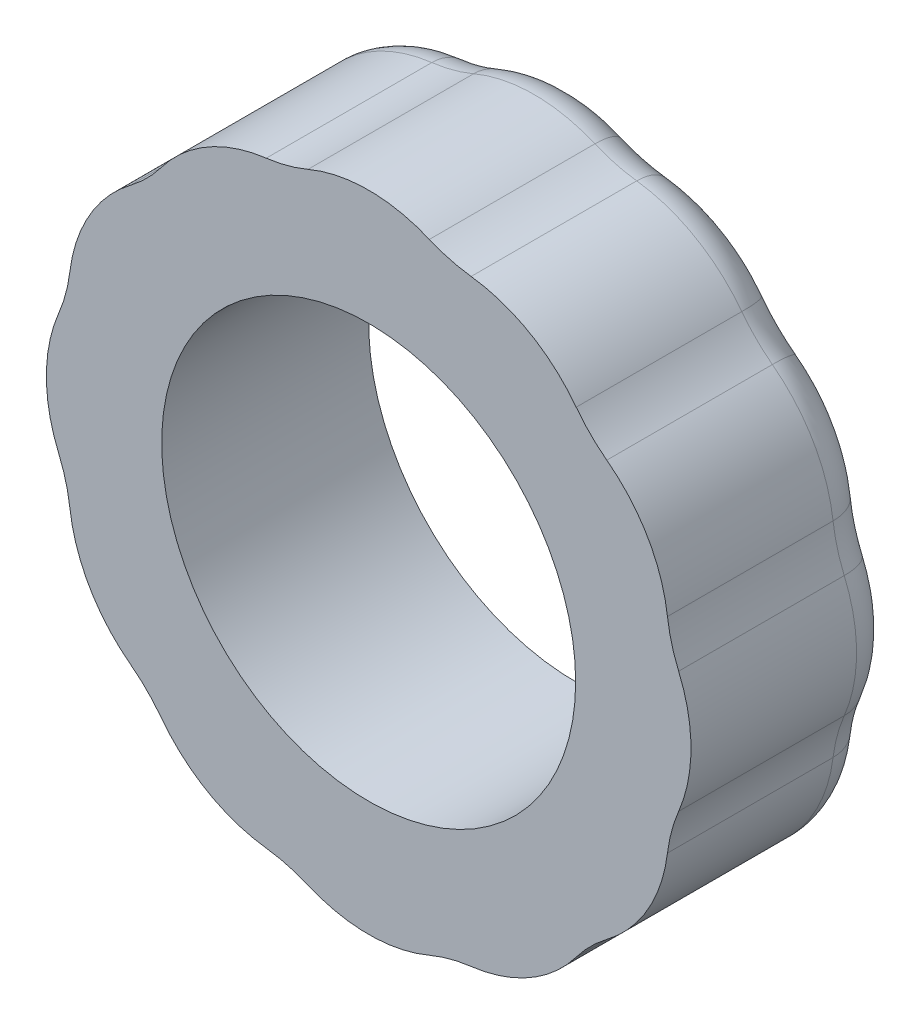
SolidWorks part; units mm, degrees
ref_plane "Front" through (0, 0, 0) normal (0, 0, 1) x (1, 0, 0)
ref_plane "Top" through (0, 0, 0) normal (0, 1, 0) x (1, 0, 0)
ref_plane "Right" through (0, 0, 0) normal (1, 0, 0) x (0, 0, -1)
sketch "Sketch1" plane through (0, 0, 0) normal (0, 0, 1) x (1, 0, 0)
  line L0 (0, 0) -> (0.3882, 1.4489) construction
  line L1 (0, 0) -> (-0.3882, 1.4489) construction
  line L2 (0, 0) -> (0, 1.5) construction
  circle A0 centre (0, 0) radius 1.5 construction
  circle A1 centre (0, 0) radius 1
  arc A2 (-0.3882, 1.4489) -> (0.3882, 1.4489) centre (0, 0.8072) cw
  arc A3 (0.3882, 1.4489) -> (1.0607, 1.0607) centre (0.4036, 0.699) cw
  arc A4 (1.0607, 1.0607) -> (1.4489, 0.3882) centre (0.699, 0.4036) cw
  arc A5 (1.4489, 0.3882) -> (1.4489, -0.3882) centre (0.8072, 0) cw
  arc A6 (1.4489, -0.3882) -> (1.0607, -1.0607) centre (0.699, -0.4036) cw
  arc A7 (1.0607, -1.0607) -> (0.3882, -1.4489) centre (0.4036, -0.699) cw
  arc A8 (0.3882, -1.4489) -> (-0.3882, -1.4489) centre (0, -0.8072) cw
  arc A9 (-0.3882, -1.4489) -> (-1.0607, -1.0607) centre (-0.4036, -0.699) cw
  arc A10 (-1.0607, -1.0607) -> (-1.4489, -0.3882) centre (-0.699, -0.4036) cw
  arc A11 (-1.4489, -0.3882) -> (-1.4489, 0.3882) centre (-0.8072, 0) cw
  arc A12 (-1.4489, 0.3882) -> (-1.0607, 1.0607) centre (-0.699, 0.4036) cw
  arc A13 (-1.0607, 1.0607) -> (-0.3882, 1.4489) centre (-0.4036, 0.699) cw
  point P43 (0, 0)
  dimension "D1" = 3
  dimension "D2" = 2
  dimension "D4" = 0.75
  dimension "D3" = 30
  dimension "D5" = 12
extrude "Boss-Extrude1" add sketch "Sketch1" along normal mid plane 1
fillet "Fillet1" radius 0.75 12 edges at (-1.4489, -0.3882, 0) (-1.0607, -1.0607, 0) (-0.3882, -1.4489, 0) (0.3882, -1.4489, 0) (1.4489, -0.3882, 0) (1.4489, 0.3882, 0) (1.0607, -1.0607, 0) (1.0607, 1.0607, 0) (0.3882, 1.4489, 0) (-0.3882, 1.4489, 0) (-1.0607, 1.0607, 0) (-1.4489, 0.3882, 0)
fillet "Fillet2" radius 0.2 24 edges at (1.4634, 0.3921, -0.5) (1.5572, 0, -0.5) (1.4634, -0.3921, -0.5) (1.3486, -0.7786, -0.5) (1.0713, -1.0713, -0.5) (0.7786, -1.3486, -0.5) (0.3921, -1.4634, -0.5) (0, -1.5572, -0.5) (-0.3921, -1.4634, -0.5) (-0.7786, -1.3486, -0.5) (-1.0713, -1.0713, -0.5) (-1.3486, -0.7786, -0.5) (-1.4634, -0.3921, -0.5) (-1.5572, 0, -0.5) (-1.4634, 0.3921, -0.5) (-1.3486, 0.7786, -0.5) (-1.0713, 1.0713, -0.5) (-0.7786, 1.3486, -0.5) (-0.3921, 1.4634, -0.5) (0, 1.5572, -0.5) (0.3921, 1.4634, -0.5) (0.7786, 1.3486, -0.5) (1.0713, 1.0713, -0.5) (1.3486, 0.7786, -0.5)
